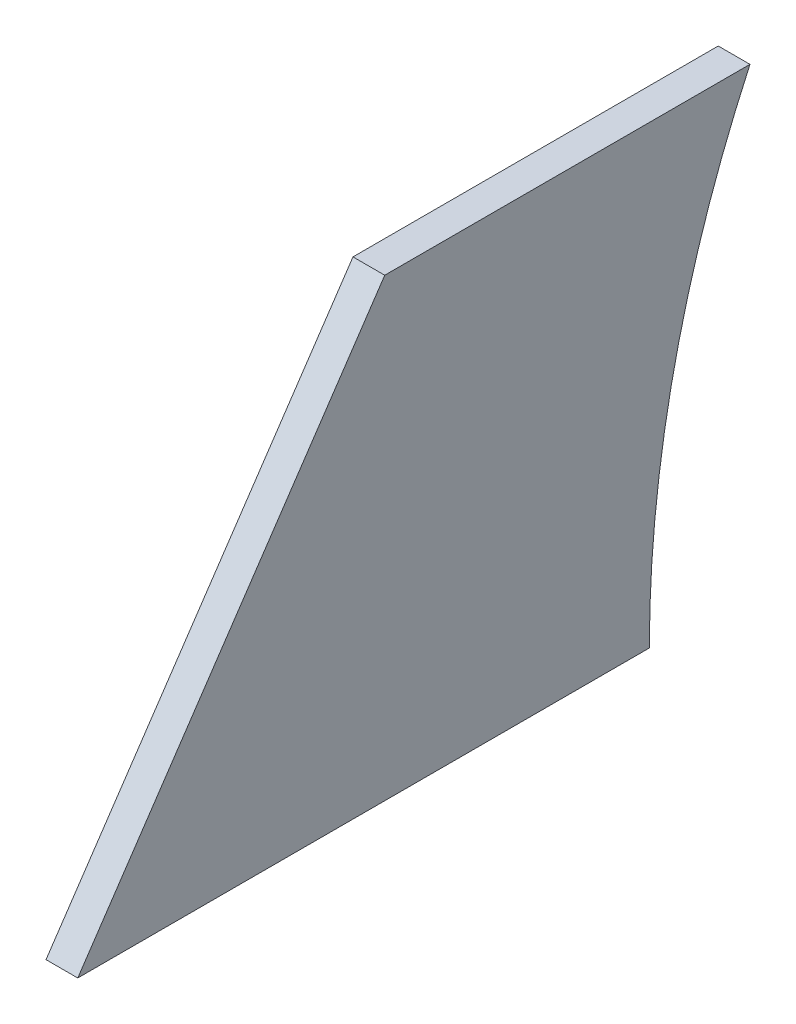
SolidWorks part; units mm, degrees
material "3.3320 (EN-AW 5019)"
ref_plane "Спереди" through (0, 0, 0) normal (0, 0, 1) x (1, 0, 0)
ref_plane "Сверху" through (0, 0, 0) normal (0, 1, 0) x (1, 0, 0)
ref_plane "Справа" through (0, 0, 0) normal (1, 0, 0) x (0, 0, -1)
sketch "Эскиз1" plane through (0, 0, 0) normal (1, 0, 0) x (0, 0, -1)
  line L0 (0, 0) -> (54, 0)
  line L1 (0, 0) -> (29, 43)
  line L2 (29, 43) -> (63.5068, 43)
  arc A0 (63.5068, 43) -> (54, 0) centre (156, 0) ccw
  point P3 (156, 0)
  dimension "D1" = 54
  dimension "D2" = 43
  dimension "D3" = 34.5068
  dimension "D4" = 29
  dimension "D5" = 102
extrude "Бобышка-Вытянуть1" add sketch "Эскиз1" along normal blind 3
